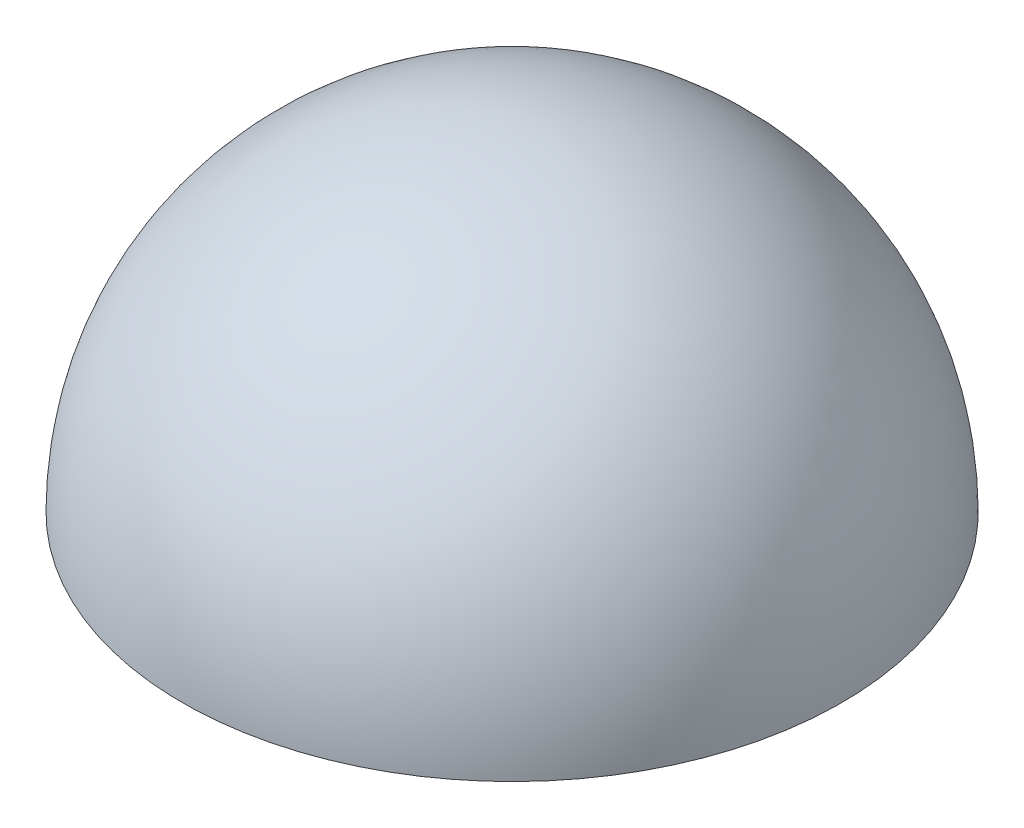
SolidWorks part; units mm, degrees
ref_plane "前视基准面" through (0, 0, 0) normal (0, 0, 1) x (1, 0, 0)
ref_plane "上视基准面" through (0, 0, 0) normal (0, 1, 0) x (1, 0, 0)
ref_plane "右视基准面" through (0, 0, 0) normal (1, 0, 0) x (0, 0, -1)
sketch "草图1" plane through (0, 0, 0) normal (0, 1, 0) x (1, 0, 0)
  line L0 (0, 0) -> (0, -94)
  arc A0 (0, 0) -> (0, -94) centre (0, -47) cw
revolve "旋转1" add sketch "草图1" angle 180 about L0
shell "抽壳3" thickness 3
